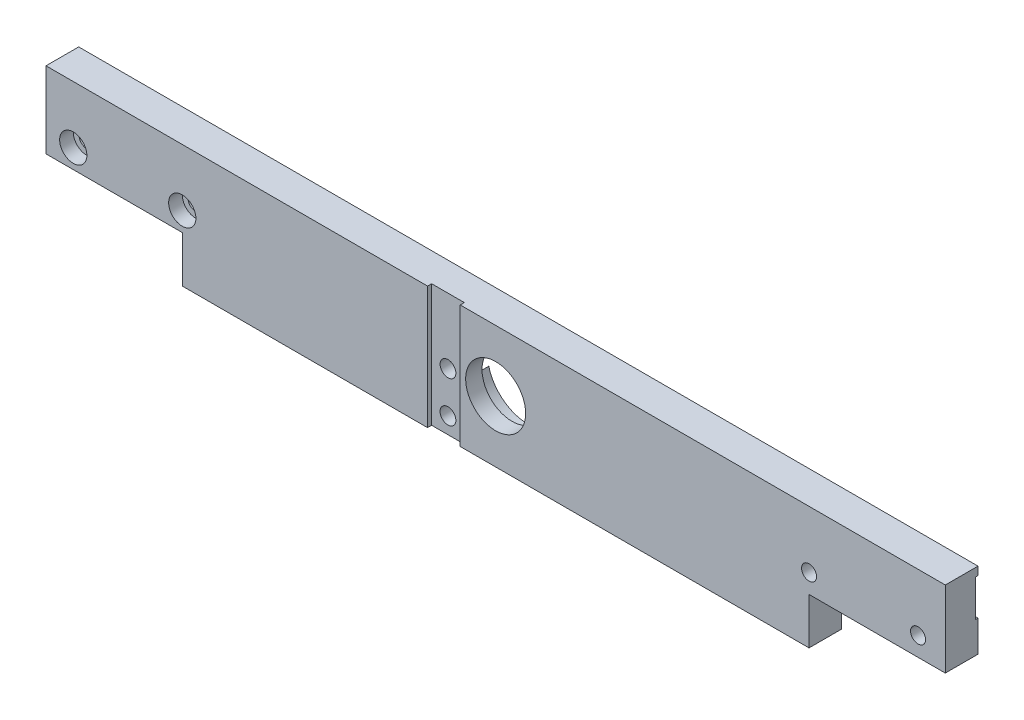
SolidWorks part; units mm, degrees
material "SKD11淬火HRC56-60"
ref_plane "前基準面" through (0, 0, 0) normal (0, 0, 1) x (1, 0, 0)
ref_plane "上基準面" through (0, 0, 0) normal (0, 1, 0) x (1, 0, 0)
ref_plane "右基準面" through (0, 0, 0) normal (1, 0, 0) x (0, 0, -1)
sketch "草图1" plane through (0, 0, 0) normal (0, 0, 1) x (1, 0, 0)
  line L1 (0, 0) -> (330, 0)
  line L2 (0, 0) -> (0, 45)
  line L3 (0, 45) -> (330, 45)
  line L4 (330, 0) -> (330, 45)
  dimension "D1" = 45
  dimension "D2" = 330
extrude "凸台-拉伸1" add sketch "草图1" along normal blind 12
hole_wizard "M5 六角凹头螺钉的柱形沉头孔1" positions "草图3" profile "草图2" counterbore size "M5" standard "ISO" end condition through all
sketch "草图3" plane through (0, 0, 12) normal (0, 0, 1) x (1, 0, 0)
  line L0 (165, 45) -> (165, 0) construction
  line L1 (330, 45) -> (0, 45) construction
  line L2 (0, 0) -> (330, 0) construction
  line L3 (0, 45) -> (0, 0) construction
  point P0 (10, 24)
  point P3 (50, 24)
  dimension "D1" = 40
  dimension "D2" = 10
  dimension "D3" = 24
sketch "草图2" plane through (10, 24, 12) normal (1, 0, 0) x (0, -1, 0)
  line L0 (0, 0) -> (0, 12)
  line L1 (0, 12) -> (2.9, 12)
  line L3 (2.9, 12) -> (2.9, 5)
  line L4 (2.9, 5) -> (5, 5)
  line L5 (5, 5) -> (5, 0)
  line L7 (5, 0) -> (0, 0)
  line L11 (0, -6.35) -> (0, 107.95) construction
  dimension "通孔孔直径" = 5.8
  dimension "通孔孔深度" = 12
  dimension "柱形沉头孔直径" = 10
  dimension "柱形沉头孔深度" = 5
sketch "草图4" plane through (0, 0, 0) normal (-1, 0, 0) x (0, 0, 1)
  line L1 (0, 45) -> (1, 45)
  line L2 (0, 45) -> (0, 28.5)
  line L3 (0, 28.5) -> (1, 28.5)
  line L4 (1, 45) -> (1, 28.5)
  dimension "D1" = 1
  dimension "D2" = 16.5
extrude "切除-拉伸1" cut sketch "草图4" against normal through all
sketch "草图5" plane through (0, 0, 1) normal (0, 0, -1) x (-1, 0, 0)
  line L0 (0, 28.5) -> (0, 45) construction
  line L1 (-330, 45) -> (0, 45)
  line L2 (-330, 45) -> (-330, 42)
  line L3 (-330, 42) -> (0, 42)
  line L4 (0, 45) -> (0, 42)
  line L5 (-330, 28.5) -> (0, 28.5) construction
  dimension "D1" = 13.5
extrude "凸台-拉伸2" add sketch "草图5" along normal blind 1
sketch "草图6" plane through (0, 0, 12) normal (0, 0, 1) x (1, 0, 0)
  line L0 (165, 45) -> (165, 0) construction
  line L1 (330, 45) -> (0, 45) construction
  line L2 (0, 0) -> (330, 0) construction
  circle A0 centre (165, 22.5) radius 11
  dimension "D1" = 22
extrude "切除-拉伸2" cut sketch "草图6" against normal through all
sketch "草图9" plane through (0, 0, 12) normal (0, 0, 1) x (1, 0, 0)
  line L0 (165, 45) -> (165, 0) construction
  line L1 (0, 0) -> (50, 0)
  line L2 (0, 0) -> (0, 17)
  line L3 (0, 17) -> (50, 17)
  line L4 (50, 0) -> (50, 17)
  line L5 (330, 45) -> (0, 45) construction
  line L6 (0, 0) -> (330, 0) construction
  line L7 (280, 0) -> (280, 17)
  line L8 (330, 17) -> (280, 17)
  line L9 (330, 0) -> (330, 17)
  line L10 (330, 0) -> (280, 0)
  dimension "D1" = 17
  dimension "D2" = 50
extrude "切除-拉伸5" cut sketch "草图9" against normal through all
sketch "草图10" plane through (0, 0, 0) normal (0, -1, 0) x (1, 0, 0)
  line L0 (50, 12) -> (280, 12) construction
  line L1 (140, 12) -> (152, 12)
  line L2 (140, 12) -> (140, 10.5)
  line L3 (140, 10.5) -> (152, 10.5)
  line L4 (152, 12) -> (152, 10.5)
  line L5 (0, 0) -> (0, 12) construction
  dimension "D1" = 12
  dimension "D2" = 1.5
  dimension "D3" = 140
extrude "切除-拉伸6" cut sketch "草图10" against normal through all
sketch "草图11" plane through (0, 0, 0) normal (0, 0, -1) x (-1, 0, 0)
  circle A0 centre (-165, 22.5) radius 15
  dimension "D1" = 30
extrude "切除-拉伸7" cut sketch "草图11" against normal blind 6
sketch "草图14" plane through (0, 0, 12) normal (0, 0, 1) x (1, 0, 0)
  line L0 (330, 17) -> (280, 17) construction
  line L1 (330, 17) -> (330, 45) construction
  circle A0 centre (280, 24) radius 2.75
  circle A1 centre (320, 24) radius 2.75
  dimension "D1" = 5.5
  dimension "D2" = 7
  dimension "D3" = 40
  dimension "D4" = 10
extrude "切除-拉伸8" cut sketch "草图14" against normal through all
hole_wizard "M5 六角凹头螺钉的柱形沉头孔2" positions "草图16" profile "草图15" counterbore size "M5" standard "ISO" end condition through all
sketch "草图16" plane through (0, 0, 0) normal (0, 0, -1) x (-1, 0, 0)
  line L0 (-50, 0) -> (-280, 0) construction
  line L1 (0, 28.5) -> (0, 17) construction
  point P0 (-146, 6)
  point P1 (-146, 21)
  dimension "D1" = 15
  dimension "D2" = 6
  dimension "D3" = 146
sketch "草图15" plane through (146, 6, 0) normal (1, 0, 0) x (0, 1, 0)
  line L0 (0, 0) -> (0, 12)
  line L1 (0, 12) -> (2.9, 12)
  line L3 (2.9, 12) -> (2.9, 5)
  line L4 (2.9, 5) -> (5, 5)
  line L5 (5, 5) -> (5, 0)
  line L7 (5, 0) -> (0, 0)
  line L11 (0, -6.35) -> (0, 107.95) construction
  dimension "通孔孔直径" = 5.8
  dimension "通孔孔深度" = 12
  dimension "柱形沉头孔直径" = 10
  dimension "柱形沉头孔深度" = 5
